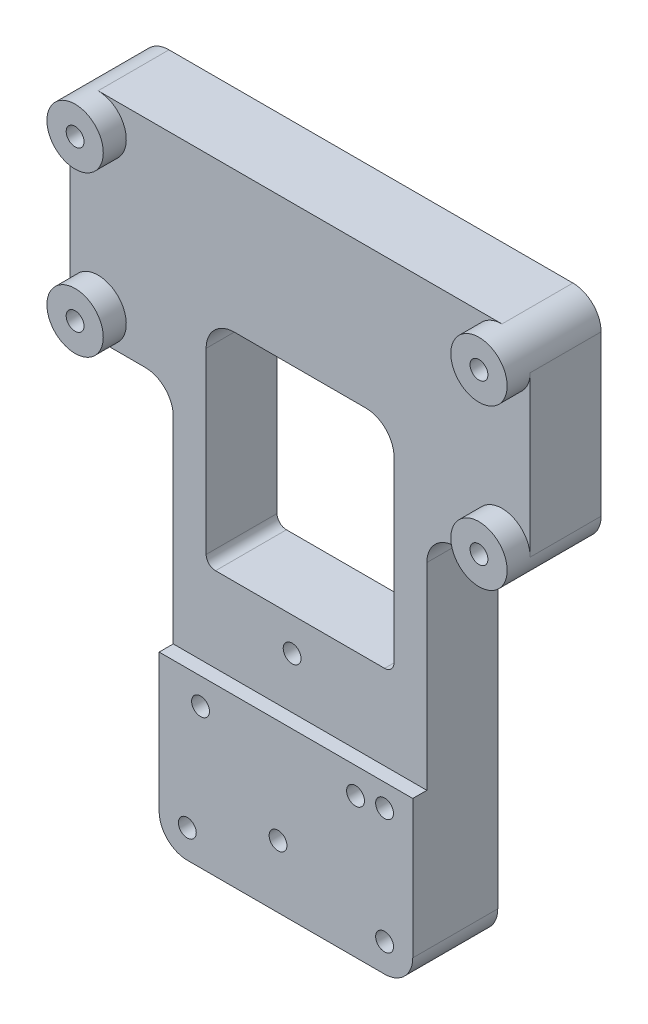
SolidWorks part; units mm, degrees
ref_plane "Front Plane" through (0, 0, 0) normal (0, 0, 1) x (1, 0, 0)
ref_plane "Top Plane" through (0, 0, 0) normal (0, 1, 0) x (1, 0, 0)
ref_plane "Right Plane" through (0, 0, 0) normal (1, 0, 0) x (0, 0, -1)
sketch "Sketch1" plane through (0, 0, 0) normal (0, 0, 1) x (1, 0, 0)
  line L1 (-23.657, 29.8) -> (-23.657, 46.8)
  line L2 (-20.657, 49.8) -> (22.343, 49.8)
  line L3 (25.343, 46.8) -> (25.343, 29.8)
  line L4 (11.343, -14.9) -> (-9.657, -14.9)
  line L5 (-12.657, -11.9) -> (-12.657, 23.8)
  line L6 (-15.657, 26.8) -> (-20.657, 26.8)
  line L7 (14.343, -11.9) -> (14.343, 23.8)
  line L8 (17.343, 26.8) -> (22.343, 26.8)
  arc A0 (-12.657, -11.9) -> (-9.657, -14.9) centre (-9.657, -11.9) ccw
  arc A1 (11.343, -14.9) -> (14.343, -11.9) centre (11.343, -11.9) ccw
  arc A2 (22.343, 26.8) -> (25.343, 29.8) centre (22.343, 29.8) ccw
  arc A3 (25.343, 46.8) -> (22.343, 49.8) centre (22.343, 46.8) ccw
  arc A4 (-20.657, 49.8) -> (-23.657, 46.8) centre (-20.657, 46.8) ccw
  arc A5 (-23.657, 29.8) -> (-20.657, 26.8) centre (-20.657, 29.8) ccw
  arc A6 (14.343, 23.8) -> (17.343, 26.8) centre (17.343, 23.8) cw
  arc A7 (-12.657, 23.8) -> (-15.657, 26.8) centre (-15.657, 23.8) ccw
  dimension "D1" = 6
  dimension "D2" = 3
extrude "Boss-Extrude1" add sketch "Sketch1" along normal offset from surface (9.05 mm away) 0.15
sketch "Sketch2" plane through (0, 0, 9.05) normal (0, 0, 1) x (1, 0, 0)
  line L0 (-0.657, 29.8) -> (2.343, 29.8) construction
  line L3 (-9.157, 34.8) -> (10.843, 34.8)
  line L4 (-9.157, 34.8) -> (-9.157, 24.8)
  line L5 (-9.157, 24.8) -> (10.843, 24.8)
  line L6 (10.843, 34.8) -> (10.843, 24.8)
  line L7 (-9.157, 34.8) -> (10.843, 24.8) construction
  line L8 (-9.157, 24.8) -> (10.843, 34.8) construction
  line L9 (-9.157, 24.8) -> (-9.157, 12.8)
  line L12 (-8.157, 11.8) -> (9.843, 11.8)
  line L13 (10.843, 12.8) -> (10.843, 24.8)
  arc A4 (-9.157, 12.8) -> (-8.157, 11.8) centre (-8.157, 12.8) ccw
  arc A5 (9.843, 11.8) -> (10.843, 12.8) centre (9.843, 12.8) ccw
  point P0 (0.843, 29.8)
  dimension "D3" = 1
  dimension "D1" = 10
  dimension "D2" = 20
  dimension "D4" = 13
extrude "Cut-Extrude1" cut sketch "Sketch2" against normal through all contours L12 A5 L13 L5 L9 A4 | L6 L3 L4 L5
fillet "Fillet1" radius 3 2 edges at (10.843, 34.8, 4.525) (-9.157, 34.8, 4.525)
sketch "Sketch4" plane through (0, 0, 9.05) normal (0, 0, 1) x (1, 0, 0)
  circle A0 centre (22.343, 29.8) radius 3
  circle A1 centre (22.343, 46.8) radius 3
  circle A2 centre (-20.657, 46.8) radius 3
  circle A3 centre (-20.657, 29.8) radius 3
extrude "Boss-Extrude2" add sketch "Sketch4" along normal up to surface (0.95 mm away)
sketch "Sketch3" plane through (0, 0, 9.05) normal (0, 0, 1) x (1, 0, 0)
  line L7 (14.343, 2.8) -> (-12.657, 2.8)
  line L8 (-8.157, 11.8) -> (9.843, 11.8) construction
  line L15 (-20.657, 26.8) -> (-15.657, 26.8)
  line L16 (-12.657, 23.8) -> (-12.657, -11.9)
  line L17 (-9.657, -14.9) -> (11.343, -14.9)
  line L18 (14.343, -11.9) -> (14.343, 23.8)
  line L19 (17.343, 26.8) -> (22.343, 26.8)
  line L20 (25.343, 29.8) -> (25.343, 46.8)
  line L21 (22.343, 49.8) -> (-20.657, 49.8)
  line L22 (-23.657, 46.8) -> (-23.657, 29.8)
  line L23 (-20.657, 26.8) -> (-15.657, 26.8)
  line L24 (-12.657, 23.8) -> (-12.657, -11.9)
  line L25 (-9.657, -14.9) -> (11.343, -14.9)
  line L26 (14.343, -11.9) -> (14.343, 23.8)
  line L27 (17.343, 26.8) -> (22.343, 26.8)
  line L28 (25.343, 29.8) -> (25.343, 46.8)
  line L29 (22.343, 49.8) -> (-20.657, 49.8)
  line L30 (-23.657, 46.8) -> (-23.657, 29.8)
  arc A8 (-12.657, 23.8) -> (-15.657, 26.8) centre (-15.657, 23.8) ccw
  arc A9 (-12.657, -11.9) -> (-9.657, -14.9) centre (-9.657, -11.9) ccw
  arc A10 (11.343, -14.9) -> (14.343, -11.9) centre (11.343, -11.9) ccw
  arc A11 (17.343, 26.8) -> (14.343, 23.8) centre (17.343, 23.8) ccw
  arc A12 (25.343, 29.8) -> (22.343, 26.8) centre (22.343, 29.8) ccw
  arc A13 (22.343, 49.8) -> (25.343, 46.8) centre (22.343, 46.8) ccw
  arc A14 (-23.657, 46.8) -> (-20.657, 49.8) centre (-20.657, 46.8) ccw
  arc A15 (-20.657, 26.8) -> (-23.657, 29.8) centre (-20.657, 29.8) ccw
  arc A16 (-12.657, 23.8) -> (-15.657, 26.8) centre (-15.657, 23.8) ccw
  arc A17 (-12.657, -11.9) -> (-9.657, -14.9) centre (-9.657, -11.9) ccw
  arc A18 (11.343, -14.9) -> (14.343, -11.9) centre (11.343, -11.9) ccw
  arc A19 (17.343, 26.8) -> (14.343, 23.8) centre (17.343, 23.8) ccw
  arc A20 (25.343, 29.8) -> (22.343, 26.8) centre (22.343, 29.8) ccw
  arc A21 (22.343, 49.8) -> (25.343, 46.8) centre (22.343, 46.8) ccw
  arc A22 (-23.657, 46.8) -> (-20.657, 49.8) centre (-20.657, 46.8) ccw
  arc A23 (-20.657, 26.8) -> (-23.657, 29.8) centre (-20.657, 29.8) ccw
  arc M5 (10.843, 12.8) -> (9.843, 11.8) centre (9.843, 12.8) cw
  line M6 (9.843, 11.8) -> (-8.157, 11.8)
  arc M7 (-8.157, 11.8) -> (-9.157, 12.8) centre (-8.157, 12.8) cw
  line M8 (-9.157, 12.8) -> (-9.157, 31.8)
  arc M9 (-9.157, 31.8) -> (-6.157, 34.8) centre (-6.157, 31.8) cw
  line M10 (-6.157, 34.8) -> (7.843, 34.8)
  arc M11 (7.843, 34.8) -> (10.843, 31.8) centre (7.843, 31.8) cw
  line M12 (10.843, 31.8) -> (10.843, 12.8)
  line M13 (-20.657, 26.8) -> (-15.657, 26.8)
  arc M14 (-15.657, 26.8) -> (-12.657, 23.8) centre (-15.657, 23.8) cw
  line M15 (-12.657, 23.8) -> (-12.657, -11.9)
  line M19 (14.343, -11.9) -> (14.343, 23.8)
  arc M20 (14.343, 23.8) -> (17.343, 26.8) centre (17.343, 23.8) cw
  line M21 (17.343, 26.8) -> (22.343, 26.8)
  arc M22 (22.343, 26.8) -> (25.343, 29.8) centre (22.343, 29.8) cw
  line M23 (25.343, 29.8) -> (25.343, 46.8)
  arc M24 (25.343, 46.8) -> (22.343, 49.8) centre (22.343, 46.8) cw
  line M25 (22.343, 49.8) -> (-20.657, 49.8)
  arc M26 (-20.657, 49.8) -> (-23.657, 46.8) centre (-20.657, 46.8) cw
  line M27 (-23.657, 46.8) -> (-23.657, 29.8)
  arc M28 (-23.657, 29.8) -> (-20.657, 26.8) centre (-20.657, 29.8) cw
  dimension "D1" = 0
  dimension "D2" = 9
extrude "Cut-Extrude2" cut sketch "Sketch3" against normal blind 1.5 contours L7 M19 M20 M21 M22 M23 M24 M25 M26 M27 M28 M13 M14 M15 M12 M5 M6 M7 M8 M9 M10 M11
sketch "Sketch5" plane through (0, 0, 10) normal (0, 0, 1) x (1, 0, 0)
  circle A0 centre (22.343, 46.8) radius 0.95
  circle A1 centre (22.343, 29.8) radius 0.95
  circle A2 centre (-20.657, 46.8) radius 0.95
  circle A3 centre (-20.657, 29.8) radius 0.95
  circle A4 centre (-9.657, -11.9) radius 0.95
  circle A5 centre (11.343, -11.9) radius 0.95
  circle A6 centre (11.343, 0.4) radius 0.95
  circle A7 centre (0, 8.25) radius 0.95
  circle A8 centre (-8.25, 0) radius 0.95
  circle A9 centre (8.25, 0) radius 0.95
  circle A10 centre (0, -8.25) radius 0.95
  dimension "D1" = 1.9
extrude "Cut-Extrude3" cut sketch "Sketch5" against normal through all
